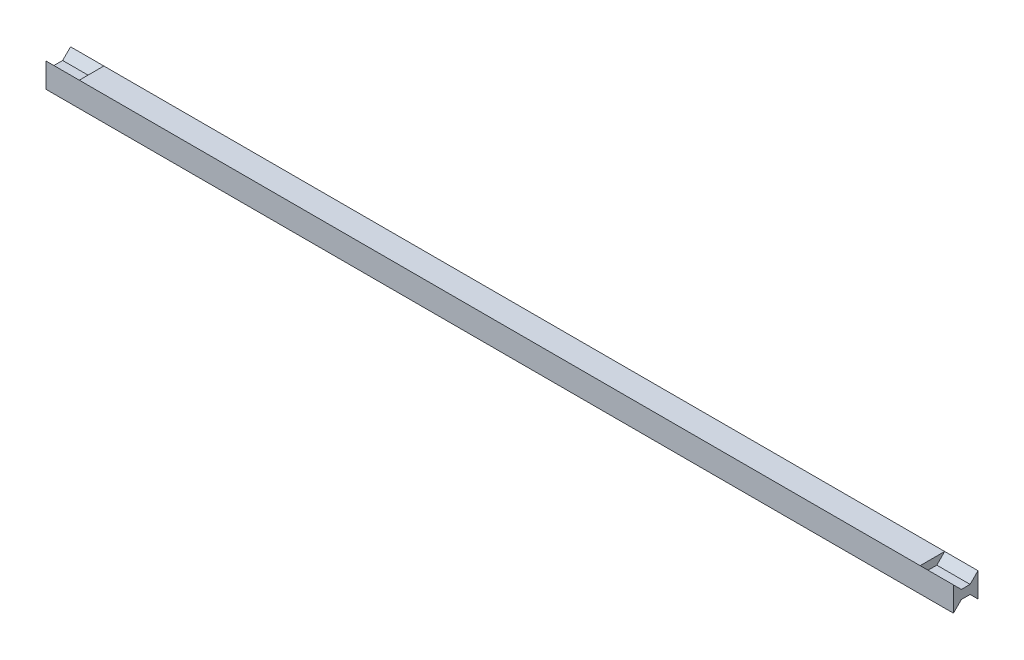
SolidWorks part; units mm, degrees
ref_plane "Přední rovina" through (0, 0, 0) normal (0, 0, 1) x (1, 0, 0)
ref_plane "Horní rovina" through (0, 0, 0) normal (0, 1, 0) x (1, 0, 0)
ref_plane "Pravá rovina" through (0, 0, 0) normal (1, 0, 0) x (0, 0, -1)
sketch "Skica1" plane through (0, 0, 0) normal (0, 1, 0) x (1, 0, 0)
  line L0 (0, 0) -> (202, 0)
  line L1 (202, 0) -> (202, 5.9)
  line L2 (202, 5.9) -> (0, 5.9)
  line L3 (0, 5.9) -> (0, 0)
  dimension "D1" = 5.9
  dimension "D2" = 202
extrude "Přidat vysunutím1" add sketch "Skica1" along normal blind 5.9
sketch "Skica2" plane through (0, 0, 0) normal (-1, 0, 0) x (0, 0, 1)
  line L0 (-5.9, 5.9) -> (0, 5.9) construction
  line L6 (-5.9, 5.9) -> (-5.9, 0)
  line L7 (-5.9, 0) -> (-4, 1.9)
  line L8 (-4, 1.9) -> (-1.9, 1.9)
  line L9 (-1.9, 1.9) -> (0, 0)
  line L10 (0, 0) -> (0, 5.9)
  line L11 (0, 5.9) -> (-1.9, 4)
  line L12 (-1.9, 4) -> (-4, 4)
  line L13 (-4, 4) -> (-5.9, 5.9)
  line L14 (0, 0) -> (-5.9, 0) construction
  dimension "D1" = 1.9
  dimension "D2" = 45
  dimension "D3" = 45
  dimension "D4" = 1.9
  dimension "D5" = 45
extrude "Přidat vysunutím2" add sketch "Skica2" along normal blind 8
sketch "Skica3" plane through (202, 0, 0) normal (1, 0, 0) x (0, 0, -1)
  line L0 (0, 0) -> (5.9, 0) construction
  line L5 (0, 5.9) -> (0, 0)
  line L6 (0, 5.9) -> (5.9, 5.9) construction
  line L7 (0, 0) -> (1.9, 1.9)
  line L8 (1.9, 1.9) -> (4, 1.9)
  line L9 (4, 1.9) -> (5.9, 0)
  line L10 (5.9, 0) -> (5.9, 5.9)
  line L11 (5.9, 5.9) -> (4, 4)
  line L12 (4, 4) -> (1.9, 4)
  line L13 (1.9, 4) -> (0, 5.9)
  dimension "D1" = 1.9
  dimension "D2" = 1.9
  dimension "D3" = 45
  dimension "D4" = 45
  dimension "D5" = 45
  dimension "D6" = 45
extrude "Přidat vysunutím3" add sketch "Skica3" along normal blind 8
